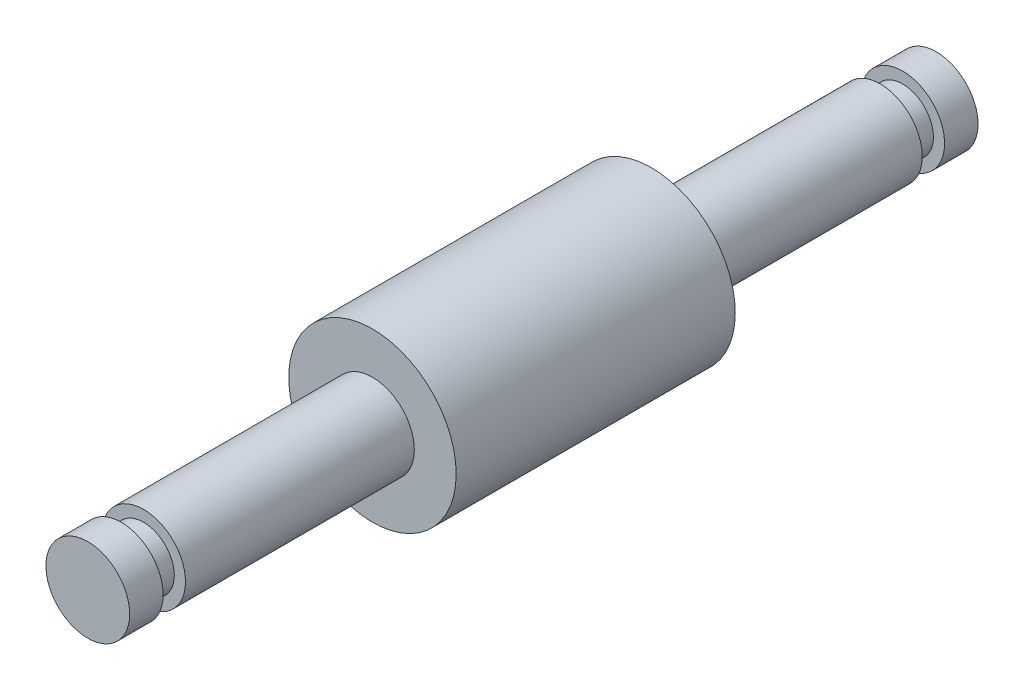
SolidWorks part; units mm, degrees
ref_plane "Ön Düzlem" through (0, 0, 0) normal (0, 0, 1) x (1, 0, 0)
ref_plane "Üst Düzlem" through (0, 0, 0) normal (0, 1, 0) x (1, 0, 0)
ref_plane "Sağ Düzlem" through (0, 0, 0) normal (1, 0, 0) x (0, 0, -1)
sketch "Çizim1" plane through (0, 0, 0) normal (0, 0, 1) x (1, 0, 0)
  circle A0 centre (0, 0) radius 15
  dimension "D1" = 30
extrude "Yükseklik-Ekstrüzyon1" add sketch "Çizim1" along normal mid plane 50
sketch "Çizim2" plane through (0, 0, 25) normal (0, 0, 1) x (1, 0, 0)
  circle A0 centre (0, 0) radius 7.5
  dimension "D1" = 15
extrude "Yükseklik-Ekstrüzyon2" add sketch "Çizim2" along normal blind 41
sketch "Çizim3" plane through (0, 0, 66) normal (0, 0, 1) x (1, 0, 0)
  circle A0 centre (0, 0) radius 5.5
  dimension "D1" = 11
extrude "Yükseklik-Ekstrüzyon3" add sketch "Çizim3" along normal blind 4
sketch "Çizim4" plane through (0, 0, 70) normal (0, 0, 1) x (1, 0, 0)
  circle A0 centre (0, 0) radius 7.5
extrude "Yükseklik-Ekstrüzyon4" add sketch "Çizim4" along normal blind 6
sketch "Çizim6" plane through (0, 0, -25) normal (0, 0, -1) x (-1, 0, 0)
  circle A0 centre (0, 0) radius 7.5
  dimension "D1" = 15
extrude "Yükseklik-Ekstrüzyon5" add sketch "Çizim6" along normal blind 41
sketch "Çizim7" plane through (0, 0, -66) normal (0, 0, -1) x (-1, 0, 0)
  circle A0 centre (0, 0) radius 5.5
  dimension "D1" = 11
extrude "Yükseklik-Ekstrüzyon6" add sketch "Çizim7" along normal blind 4
sketch "Çizim8" plane through (0, 0, -70) normal (0, 0, -1) x (-1, 0, 0)
  circle A0 centre (0, 0) radius 7.5
extrude "Yükseklik-Ekstrüzyon7" add sketch "Çizim8" along normal blind 6
